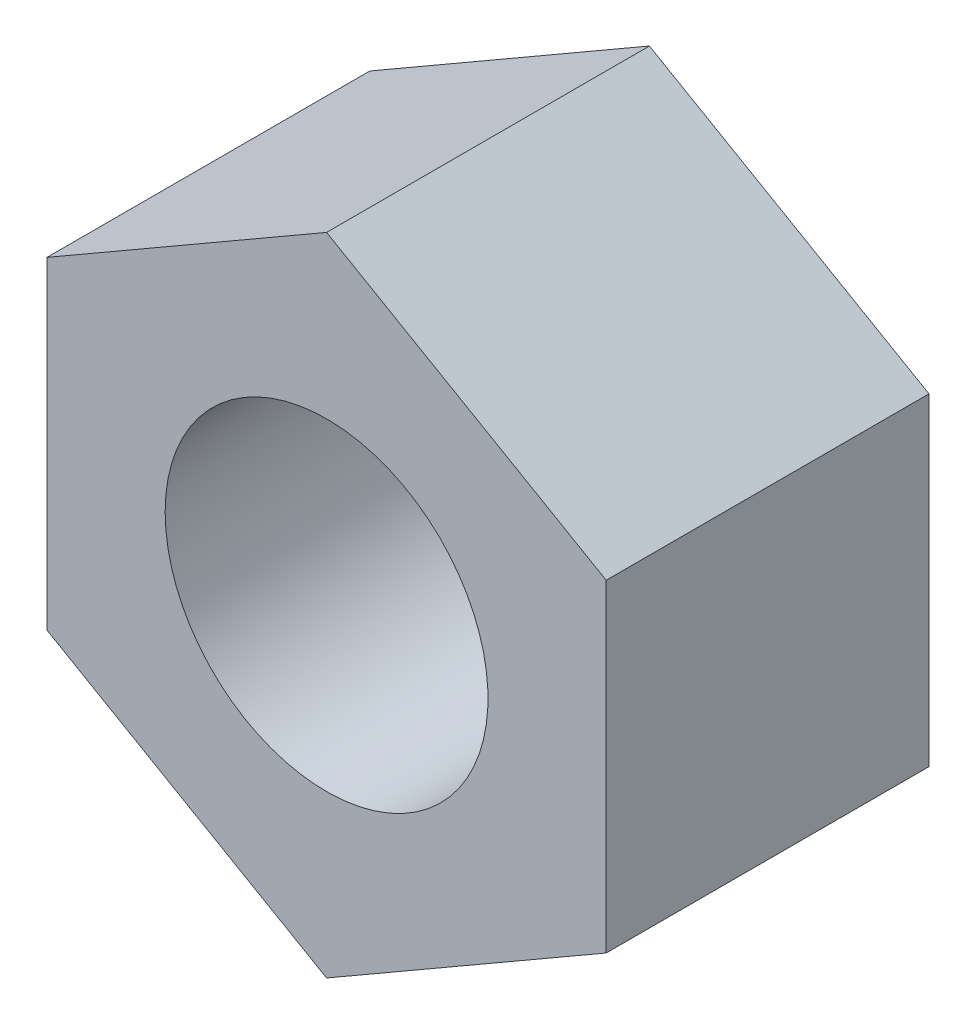
SolidWorks part; units mm, degrees
ref_plane "Front Plane" through (0, 0, 0) normal (0, 0, 1) x (1, 0, 0)
ref_plane "Top Plane" through (0, 0, 0) normal (0, 1, 0) x (1, 0, 0)
ref_plane "Right Plane" through (0, 0, 0) normal (1, 0, 0) x (0, 0, -1)
sketch "Sketch1" plane through (0, 0, 0) normal (0, 0, 1) x (1, 0, 0)
  line L1 (0, 3) -> (-2.5981, 1.5)
  line L2 (-2.5981, 1.5) -> (-2.5981, -1.5)
  line L3 (-2.5981, -1.5) -> (0, -3)
  line L4 (0, -3) -> (2.5981, -1.5)
  line L5 (2.5981, -1.5) -> (2.5981, 1.5)
  line L6 (2.5981, 1.5) -> (0, 3)
  circle A0 centre (0, 0) radius 2.5981 construction
  dimension "D1" = 3
extrude "Boss-Extrude1" add sketch "Sketch1" along normal blind 3
sketch "Sketch2" plane through (0, 0, 0) normal (0, 0, -1) x (-1, 0, 0)
  circle A0 centre (0, 0) radius 1.5
  dimension "D1" = 3
extrude "Cut-Extrude1" cut sketch "Sketch2" against normal blind 3 contours A0
